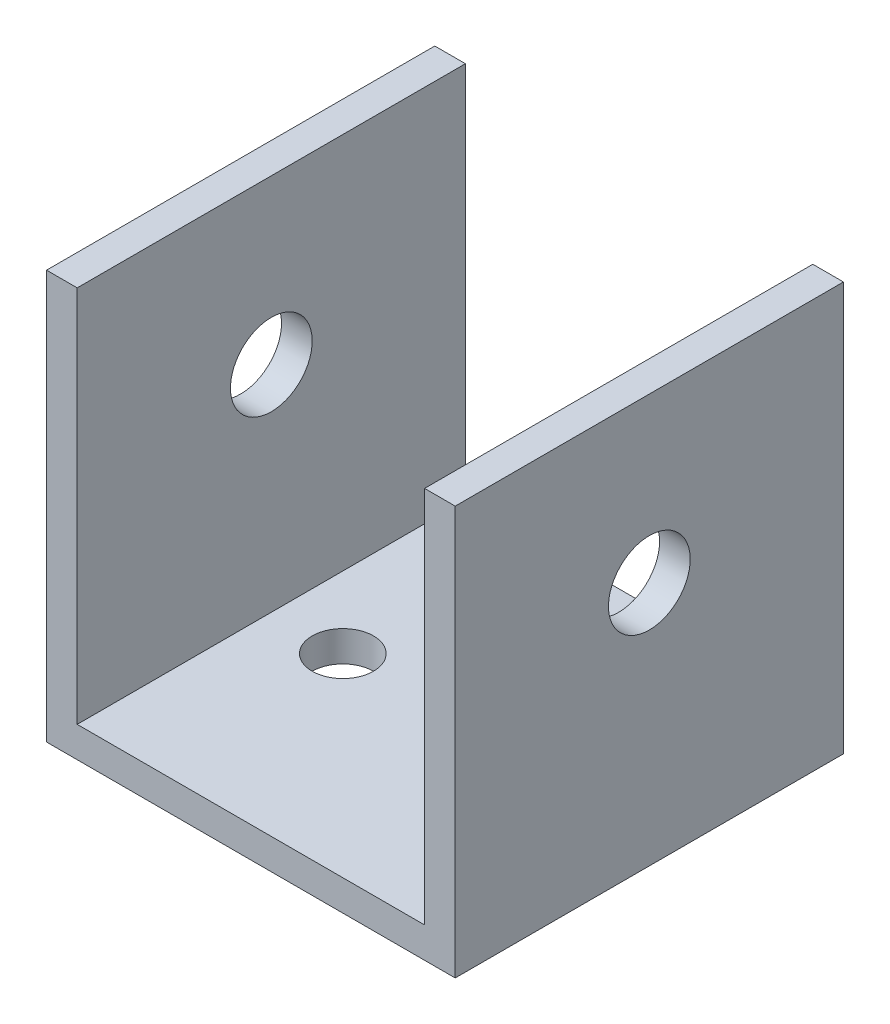
SolidWorks part; units mm, degrees
ref_plane "Plan de face" through (0, 0, 0) normal (0, 0, 1) x (1, 0, 0)
ref_plane "Plan de dessus" through (0, 0, 0) normal (0, 1, 0) x (1, 0, 0)
ref_plane "Plan de droite" through (0, 0, 0) normal (1, 0, 0) x (0, 0, -1)
sketch "Esquisse1" plane through (0, 0, 0) normal (0, 0, 1) x (1, 0, 0)
  line L0 (18.7061, -17.1121) -> (18.7061, -37.1121)
  line L1 (18.7061, -37.1121) -> (38.7061, -37.1121)
  line L2 (38.7061, -37.1121) -> (38.7061, -17.1121)
  line L3 (38.7061, -17.1121) -> (37.2061, -17.1121)
  line L4 (37.2061, -17.1121) -> (37.2061, -35.6121)
  line L5 (37.2061, -35.6121) -> (20.2061, -35.6121)
  line L6 (20.2061, -35.6121) -> (20.2061, -17.1121)
  line L7 (20.2061, -17.1121) -> (18.7061, -17.1121)
  dimension "D1" = 1.5
  dimension "D2" = 1.5
  dimension "D3" = 1.5
  dimension "D4" = 20
  dimension "D5" = 20
  dimension "D6" = 20
extrude "Extrusion1" add sketch "Esquisse1" along normal blind 19
sketch "Esquisse2" plane through (0, -37.1121, 0) normal (0, -1, 0) x (1, 0, 0)
  line L0 (33.7061, 9.5) -> (23.7061, 9.5) construction
  line L1 (38.7061, 19) -> (38.7061, 0) construction
  line L2 (18.7061, 0) -> (38.7061, 0) construction
  circle A0 centre (23.7061, 9.5) radius 1.5
  circle A1 centre (33.7061, 9.5) radius 1.5
  dimension "D2" = 5
  dimension "D1" = 10
  dimension "D3" = 9.5
extrude "Extrusion2" cut sketch "Esquisse2" against normal blind 5
sketch "Esquisse3" plane through (18.7061, 0, 0) normal (-1, 0, 0) x (0, 0, 1)
  line L0 (19, -17.1121) -> (19, -37.1121) construction
  line L1 (19, -37.1121) -> (0, -37.1121) construction
  circle A0 centre (9.5, -25.1121) radius 2
  dimension "D1" = 9.5
  dimension "D2" = 12
extrude "Extrusion3" cut sketch "Esquisse3" against normal through all
